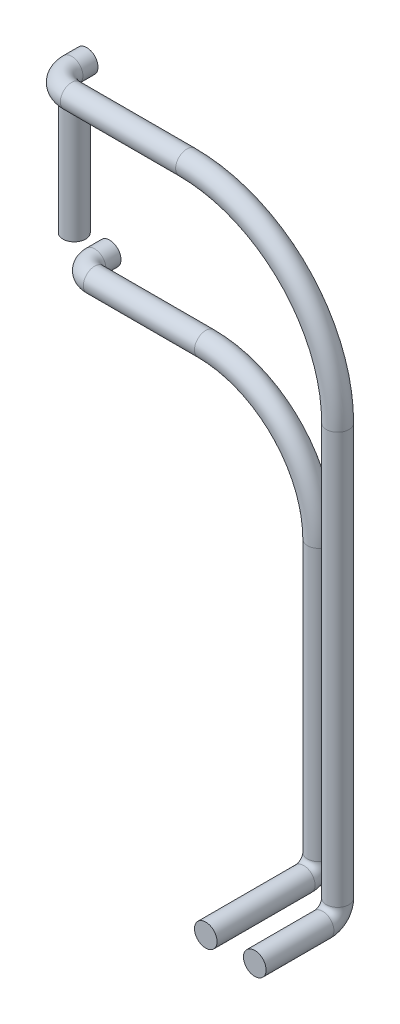
SolidWorks part; units mm, degrees
ref_plane "Front Plane" through (0, 0, 0) normal (0, 0, 1) x (1, 0, 0)
ref_plane "Top Plane" through (0, 0, 0) normal (0, 1, 0) x (1, 0, 0)
ref_plane "Right Plane" through (0, 0, 0) normal (1, 0, 0) x (0, 0, -1)
sketch3d "3DSketch1"
  line L0 (0, 0, 0) -> (0, 0, -13)
  line L1 (0, 2, -15) -> (0, 38, -15)
  line L2 (-15, 53, -15) -> (-29.75, 53, -15)
  line L3 (-31.75, 53, -17) -> (-31.75, 53, -19)
  arc A0 (0, 0, -13) -> (0, 2, -15) centre (0, 2, -13) ccw
  arc A1 (-29.75, 53, -15) -> (-31.75, 53, -17) centre (-29.75, 53, -17) ccw
  arc A2 (-15, 53, -15) -> (0, 38, -15) centre (-15, 38, -15) ccw
  point P8 (0, 0, -15)
  point P9 (2, 2, -13)
  point P12 (-31.75, 53, -15)
  point P13 (-29.75, 51, -17)
  point P16 (0, 53, -15)
  point P17 (-15, 38, -30)
  dimension "D5" = 2
  dimension "D6" = 15
  dimension "D1" = 53
  dimension "D2" = 15
  dimension "D3" = 31.75
  dimension "D4" = 4
sketch3d "3DSketch2"
  line L0 (-36.45, 53, -19) -> (-36.45, 69, -19)
  dimension "D1" = 16
  dimension "D2" = 4.7
sketch3d "3DSketch3"
  line L0 (6.5, 0, 0) -> (6.5, 0, -9)
  line L1 (0, 0, 0) -> (0, 0, -13) construction
  line L2 (6.5, 2, -11) -> (6.5, 56.6, -11)
  line L3 (0, 2, -15) -> (0, 38, -15) construction
  line L4 (-13.5, 76.6, -11) -> (-28.8, 76.6, -11)
  line L5 (-31.8, 76.6, -14) -> (-31.8, 76.6, -16)
  arc A0 (6.5, 0, -9) -> (6.5, 2, -11) centre (6.5, 2, -9) ccw
  arc A1 (-28.8, 76.6, -11) -> (-31.8, 76.6, -14) centre (-28.8, 76.6, -14) ccw
  arc A2 (6.5, 56.6, -11) -> (-13.5, 76.6, -11) centre (-13.5, 56.6, -11) ccw
  point P11 (6.5, 0, -11)
  point P13 (8.5, 2, -9)
  point P16 (-31.8, 76.6, -11)
  point P17 (-31.8, 76.6, -11)
  point P20 (6.5, 76.6, -11)
  point P21 (-13.5, 56.6, 9)
  point P22 (-28.8, 73.6, -14)
  dimension "D6" = 2
  dimension "D7" = 20
  dimension "D8" = 3
  dimension "D1" = 6.5
  dimension "D2" = 76.6
  dimension "D3" = 11
  dimension "D4" = 38.3
  dimension "D5" = 5
sweep "Sweep1" add path "3DSketch1" circular profile diameter 3 parameters "D3"=3
sweep "Sweep2" add path "3DSketch2" circular profile diameter 3 parameters "D3"=3
sweep "Sweep3" add path "3DSketch3" circular profile diameter 3 parameters "D3"=3
other "Freeze***"
